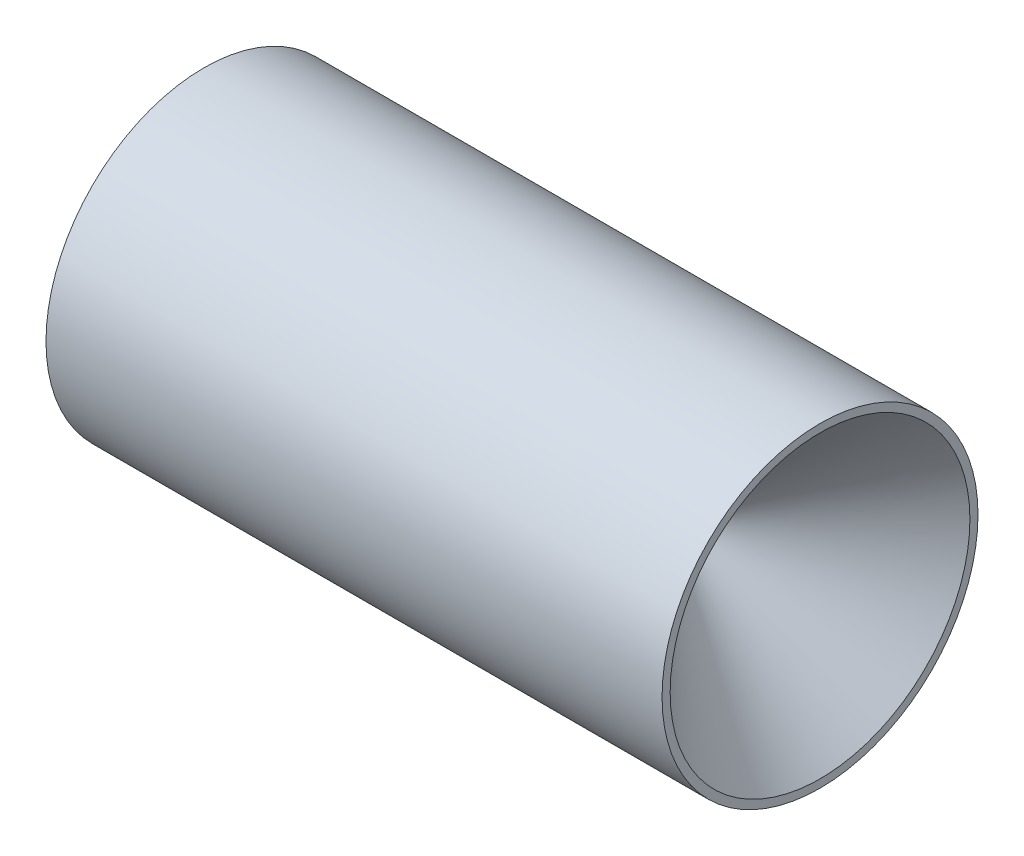
SolidWorks part; units mm, degrees
material "C (Graphite)"
ref_plane "Front Plane" through (0, 0, 0) normal (0, 0, 1) x (1, 0, 0)
ref_plane "Top Plane" through (0, 0, 0) normal (0, 1, 0) x (1, 0, 0)
ref_plane "Right Plane" through (0, 0, 0) normal (1, 0, 0) x (0, 0, -1)
sketch "Sketch1" plane through (0, 0, 0) normal (0, 0, 1) x (1, 0, 0)
  line L0 (11.2724, 0) -> (-90.9907, 0) construction
  line L7 (-78, 20) -> (0, 20)
  line L16 (-20.2124, 2.848) -> (-78, 18.3321)
  line L17 (-78, 18.3321) -> (-78, 20)
  line L18 (-16.128, 2.848) -> (-20.2124, 2.848)
  line L19 (0, 20) -> (0, 18.9761)
  line L20 (0, 18.9761) -> (-16.128, 2.848)
  point P7 (-16.128, 2.848)
  dimension "D2" = 45
  dimension "D3" = 78
  dimension "D1" = 40
  dimension "D4" = 15
revolve "Revolve1" add sketch "Sketch1" angle 360 about L0
